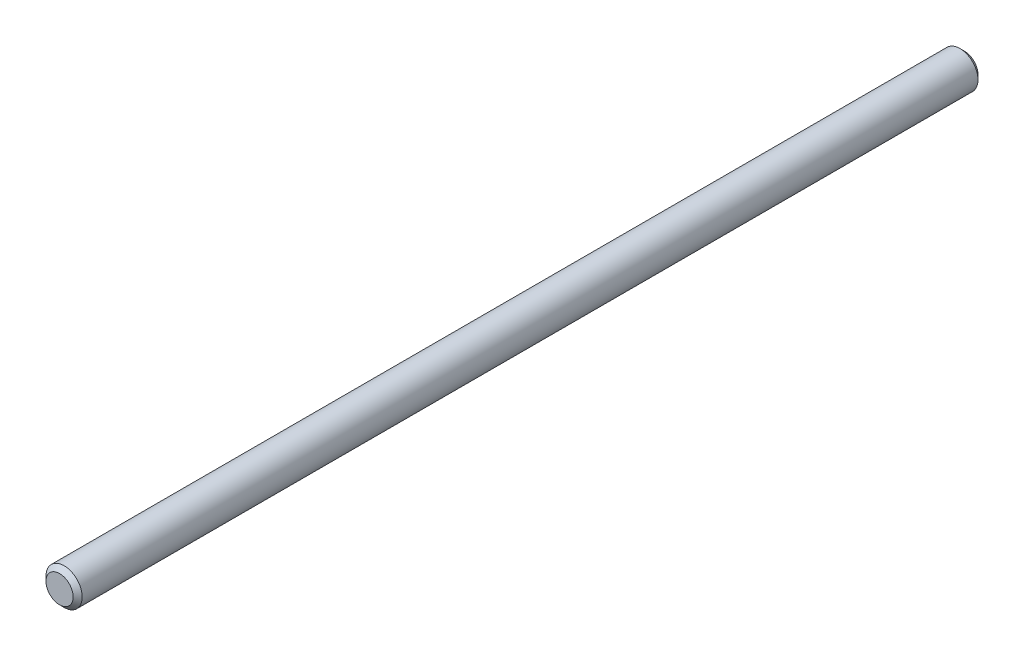
SolidWorks part; units mm, degrees
material "1060 Alloy"
ref_plane "Front Plane" through (0, 0, 0) normal (0, 0, 1) x (1, 0, 0)
ref_plane "Top Plane" through (0, 0, 0) normal (0, 1, 0) x (1, 0, 0)
ref_plane "Right Plane" through (0, 0, 0) normal (1, 0, 0) x (0, 0, -1)
sketch "Sketch1" plane through (0, 0, 0) normal (0, 0, 1) x (1, 0, 0)
  circle A0 centre (0, 0) radius 4
  dimension "D1" = 8
extrude "body" add sketch "Sketch1" along normal blind 200
chamfer "end_chamfers" distance 1 angle 45 2 edges at (4, 0, 0) (4, 0, 200)
